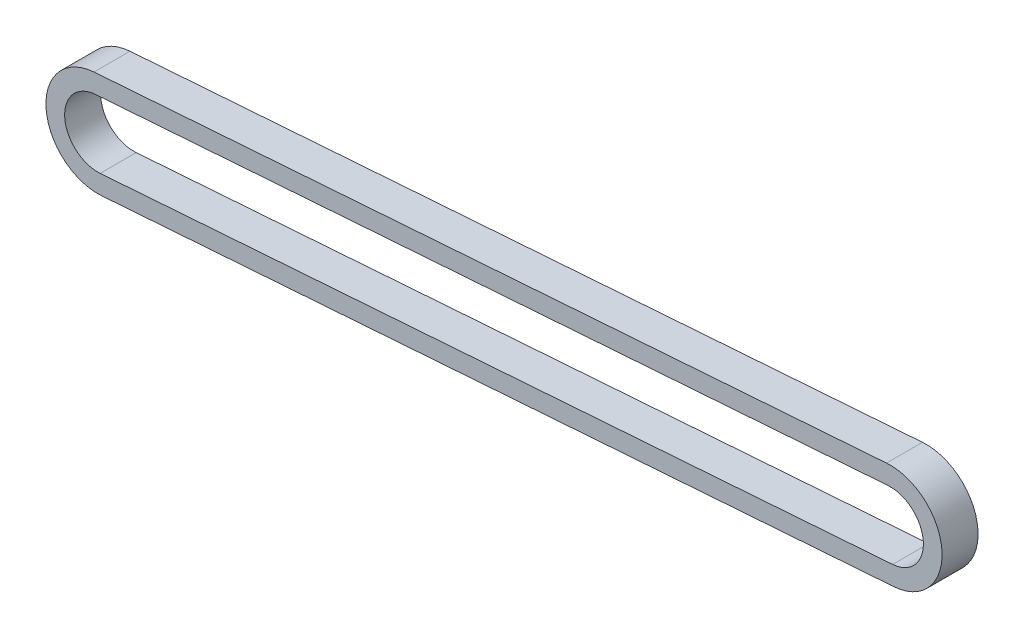
SolidWorks part; units mm, degrees
ref_plane "Front Plane" through (0, 0, 0) normal (0, 0, 1) x (1, 0, 0)
ref_plane "Top Plane" through (0, 0, 0) normal (0, 1, 0) x (1, 0, 0)
ref_plane "Right Plane" through (0, 0, 0) normal (1, 0, 0) x (0, 0, -1)
sketch "Sketch1" plane through (0, 0, 0) normal (0, 0, 1) x (1, 0, 0)
  line L0 (0.2117, -2.9133) -> (70.1314, 2.1667)
  line L1 (69.708, 7.9933) -> (-0.2117, 2.9133)
  line L2 (69.5884, 9.64) -> (-0.3313, 4.56)
  line L3 (0.3313, -4.56) -> (70.251, 0.52)
  circle A0 centre (0, 0) radius 2.921 construction
  circle A1 centre (69.9197, 5.08) radius 2.921 construction
  arc A2 (70.1314, 2.1667) -> (69.708, 7.9933) centre (69.9197, 5.08) ccw
  arc A3 (-0.2117, 2.9133) -> (0.2117, -2.9133) centre (0, 0) ccw
  arc A4 (-0.3313, 4.56) -> (0.3313, -4.56) centre (0, 0) ccw
  arc A5 (70.251, 0.52) -> (69.5884, 9.64) centre (69.9197, 5.08) ccw
  dimension "D1" = 5.842
  dimension "D2" = 5.842
  dimension "D5" = 158.5612
  dimension "D7" = 168.9347
  dimension "D3" = 70.104
  dimension "D4" = 5.08
  dimension "D6" = 1.651
extrude "Boss-Extrude1" add sketch "Sketch1" along normal blind 3.175
